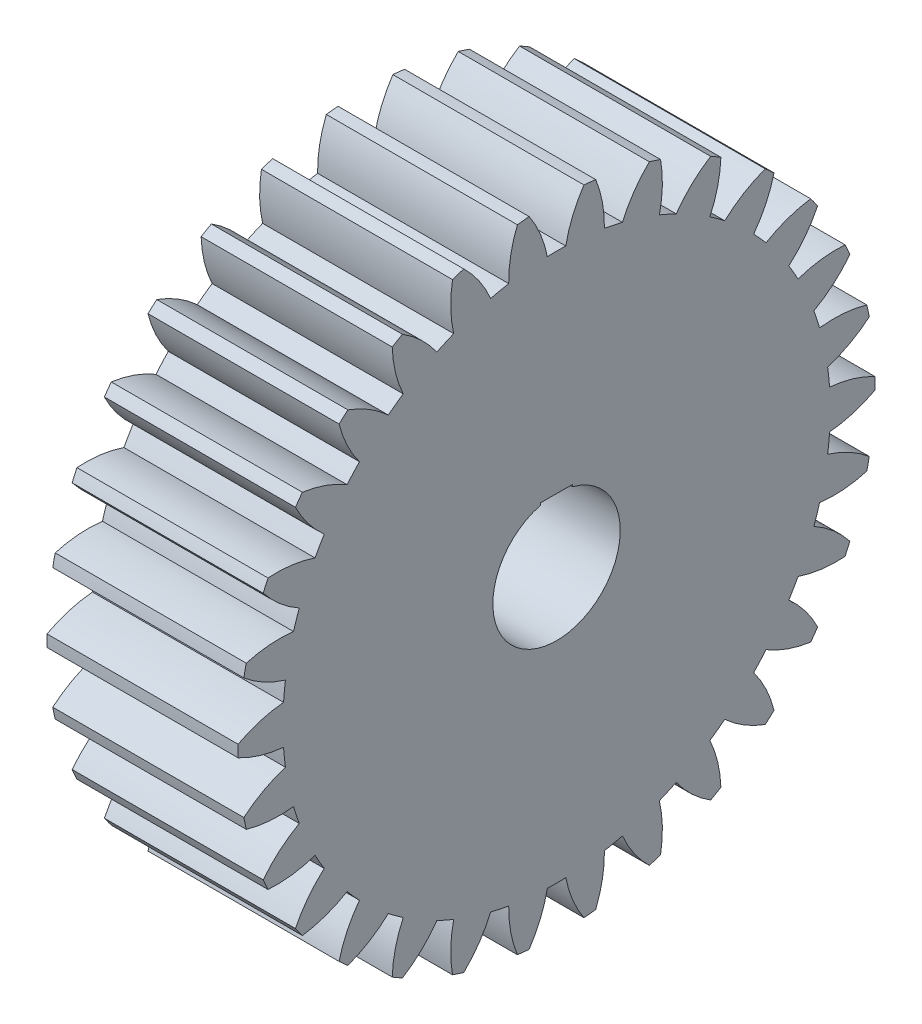
SolidWorks part; units mm, degrees
ref_plane "Plane1" through (0, 0, 0) normal (0, 0, 1) x (1, 0, 0)
ref_plane "Plane2" through (0, 0, 0) normal (0, 1, 0) x (1, 0, 0)
ref_plane "Plane3" through (0, 0, 0) normal (1, 0, 0) x (0, 0, -1)
other "Configuration Table"
sketch "HoldingSke" plane through (0, 0, 0) normal (0, 1, 0) x (1, 0, 0)
  line L0 (0, 0) -> (0.6928, -0.4)
  line L1 (-15, 0) -> (100, 0) construction
  line L2 (0, 0) -> (-2.1039, 2.3779)
  line L3 (0, 0) -> (-11.863, 4.5341)
  line L4 (0, 0) -> (7.479, 4.318)
  line L5 (0, 0) -> (-7.4956, -2.7956)
  line L6 (0, 0) -> (-9.9476, -6.7116)
  line L7 (-2.1039, 2.3779) -> (0.4791, 14.0966)
  line L8 (-76.2, 54.61) -> (-75.2, 54.61)
  line L9 (-71.009, 38.7566) -> (-53.1078, 45.2721)
  line L10 (-76.2, 71.12) -> (104.1128, 71.12)
  line L11 (0, 0) -> (-12, 0)
  line L12 (-76.2, 101.6) -> (-76.155, 101.6)
  line L13 (24.9733, 27.94) -> (52.9518, 28.4284)
  line L14 (24.9733, 27.94) -> (24.9743, 27.94)
  line L15 (24.9733, 27.94) -> (100.4006, 29.5858)
  line L16 (-63.627, -1.25) -> (-12.827, -1.25)
  circle A0 centre (0, 0) radius 3
  circle A1 centre (0, 0) radius 5
  circle A2 centre (0, 0) radius 5
  circle A3 centre (0, 0) radius 3
  dimension "MHD" = 10
  dimension "Hub_dia" = 10
  dimension "Bore" = 6
  dimension "MBD" = 6
  dimension "Num_teeth" = 30
  dimension "Pitch" = 0.8
  dimension "Overall_len" = 8
  dimension "Show_teeth" = 30
  dimension "Thickness" = 12
  dimension "OAL" = 12.0001
  dimension "T_dim" = 1
  dimension "Ap" = 20
  dimension "H" = 19.05
  dimension "Pitch_radius" = 180.3128
  dimension "Width" = 12
  dimension "Backlash" = 0.045
  dimension "Addendum_fac" = 1
  dimension "Dedendum_fac" = 1.25
  dimension "Clearance_fac" = 0.25
  dimension "Dedendum_add" = 0.001
  dimension "Module" = 1.25
sketch "BasProSke" plane through (0, 0, 0) normal (0, 1, 0) x (1, 0, 0)
  line L0 (-10, 0) -> (60, 0) construction
  line L1 (0, 0) -> (0, 20)
  line L2 (0, 0) -> (12, 0)
  line L3 (12, 0) -> (12, 20)
  line L4 (12, 20) -> (0, 20)
  dimension "Thickness" = 12
  dimension "Diameter" = 40
revolve "Base-Revolve" add sketch "BasProSke" angle 360 about L0
sketch "TooCutSke" plane through (0, 0, 0) normal (1, 0, 0) x (0, 0, -1)
  line L1 (0, 0) -> (0, 107) construction
  line L2 (0, 0) -> (-1.06, 18.72) construction
  line L3 (0, 0) -> (-3.9153, 37.2513) construction
  line L4 (-1.06, 18.72) -> (-1.9576, 18.6257) construction
  arc A0 (0.579, 17.1767) -> (-0.579, 17.1767) centre (0, 0) ccw
  arc A1 (1.7381, 19.9498) -> (-1.7381, 19.9498) centre (0, 0) ccw
  circle A2 centre (0, 0) radius 18.75 construction
  circle A3 centre (0, 0) radius 17.6192 construction
  arc A4 (-0.579, 17.1767) -> (-1.7381, 19.9498) centre (-7.9381, 15.7297) ccw
  arc A5 (1.7381, 19.9498) -> (0.579, 17.1767) centre (7.9381, 15.7297) ccw
  dimension "Root_dia" = 34.373
  dimension "Overcut_dia" = 40.0508
  dimension "Pitch_dia" = 37.5
  dimension "Base_dia" = 35.2385
  dimension "Flank_rad" = 7.5
  dimension "Half_ang" = 6
  dimension "Half_CT" = 0.9025
extrude "ToothCut" cut sketch "TooCutSke" along normal through all
fillet "Breaks" [suppressed] radius 0.025
fillet "RootFillets" [suppressed] radius 0.3135
pattern_circular "TeethCuts" count 30 every 12 about axis through (-10, 0, 0) along (1, 0, 0) of "ToothCut", "RootFillets", "Breaks"
sketch "HubNeaOneSke" plane through (0, 0, 0) normal (-1, 0, 0) x (0, 0, 1)
  circle A0 centre (0, 0) radius 5
  dimension "Diameter" = 10
extrude "HubNearOne" add sketch "HubNeaOneSke" along normal blind 5.0001
sketch "HubNeaBotSke" plane through (0, 0, 0) normal (-1, 0, 0) x (0, 0, 1)
  circle A0 centre (0, 0) radius 5
  dimension "Diameter" = 10
extrude "HubNearBoth" [suppressed] add sketch "HubNeaBotSke" along normal blind 2.5
ref_plane "FarPln" through (12, 0, 0) normal (1, 0, 0) x (0, 0, -1)
sketch "HubFarSke" plane through (12, 0, 0) normal (1, 0, 0) x (0, 0, -1)
  circle A0 centre (0, 0) radius 5
  dimension "Diameter" = 10
extrude "HubFar" [suppressed] add sketch "HubFarSke" along normal blind 2.5
sketch "BorSke" plane through (0, 0, 0) normal (1, 0, 0) x (0, 0, -1)
  circle A0 centre (0, 0) radius 3
  dimension "Diameter" = 6
extrude "Bore" cut sketch "BorSke" along normal mid plane 24.0001
sketch "KeySke" plane through (0, 0, 0) normal (1, 0, 0) x (0, 0, -1)
  line L0 (-1, 0) -> (-1, 4)
  line L1 (-1, 4) -> (1, 4)
  line L2 (1, 4) -> (1, 0)
  line L3 (0, 0) -> (0, 34) construction
  line L4 (-1, 0) -> (1, 0)
  dimension "Offset" = 4
  dimension "Width" = 2
extrude "Keyway" cut sketch "KeySke" along normal mid plane 24.0001
pattern_circular "Keyway2" [suppressed] count 2 every 90 about axis through (-10, 0, 0) along (1, 0, 0)
sketch "Sketch1" plane through (0, 4, 0) normal (0, -1, 0) x (1, 0, 0)
  line L0 (-5.0001, 0) -> (0, 0) construction
  line L1 (-5.0001, 5) -> (-5.0001, -5) construction
  line L2 (0, 0.579) -> (0, -0.579) construction
  circle A0 centre (-2.5, 0) radius 1.45
  dimension "D1" = 2.9
extrude "Cut-Extrude1" cut sketch "Sketch1" against normal blind 10
sketch "Sketch2" plane through (-5.0001, 0, 0) normal (-1, 0, 0) x (0, 0, 1)
  circle A0 centre (0, 0) radius 4
  dimension "D1" = 8
extrude "Cut-Extrude2" cut sketch "Sketch2" against normal blind 20
sketch "Sketch3" plane through (0, 0, 0) normal (-1, 0, 0) x (0, 0, 1)
  circle A0 centre (0, 0) radius 7
  arc A1 (-1, 3.873) -> (1, 3.873) centre (0, 0) ccw construction
  circle A2 centre (0, 0) radius 5
  dimension "D1" = 3
extrude "Boss-Extrude1" add sketch "Sketch3" along normal blind 5
sketch "Sketch4" plane through (0, 0, 0) normal (0, 1, 0) x (1, 0, 0)
  line L0 (-2.5, 0) -> (0, 0) construction
  line L1 (0, 0.579) -> (0, -0.579) construction
  circle A0 centre (-2.5, 0) radius 1.4
  dimension "D1" = 2.8
  dimension "D2" = 2.5
extrude "Cut-Extrude3" cut sketch "Sketch4" along normal blind 15
equation "' \"Module@HoldingSke\" = 6.35"
equation "' \"Num_teeth@HoldingSke\" = 12"
equation "' \"Ap@HoldingSke\" =  20"
equation "' \"Ap@HoldingSke\" = 20"
equation "' \"Width@HoldingSke\" = 0.5 * 25.4"
equation "' \"Hub_dia@HoldingSke\"= 1 * 25.4"
equation "' \"Hub_dia@HoldingSke\" = 1 * 25.4"
equation "' \"Overall_len@HoldingSke\" = 1.0 * 25.4"
equation "' \"Bore@HoldingSke\" = 0.75 * 25.4"
equation "' \"T_dim@HoldingSke\" = 0.1 * 25.4"
equation "' \"Width@KeySke\" = 0.25 * 25.4"
equation "' \"Show_teeth@HoldingSke\" = 13"
equation "' \"Backlash@HoldingSke\" = 0.009 * 25.4"
equation "' \"Addendum_fac@HoldingSke\" = 1.0"
equation "' \"Dedendum_fac@HoldingSke\" = 1.25"
equation "' \"Dedendum_add@HoldingSke\" = 0.00005 * 25.4"
equation "' \"Clearance_fac@HoldingSke\" = 0.25"
equation "\"Pitch@HoldingSke\" = 1 / \"Module@HoldingSke\""
equation "\"Overcut_dia@TooCutSke\" = (\"Num_teeth@HoldingSke\" + 2 * \"Addendum_fac@HoldingSke\") / \"Pitch@HoldingSke\" + 0.002 * 25.4"
equation "\"Pitch_dia@TooCutSke\" = \"Num_teeth@HoldingSke\" / \"Pitch@HoldingSke\""
equation "\"Base_dia@TooCutSke\" = \"Num_teeth@HoldingSke\" / \"Pitch@HoldingSke\" * cos((\"Ap@HoldingSke\"  * 3.14159265 / 180))"
equation "\"Root_dia@TooCutSke\" = (\"Num_teeth@HoldingSke\" + 2) / \"Pitch@HoldingSke\" - 2 * (\"Addendum_fac@HoldingSke\" + \"Dedendum_fac@HoldingSke\") / \"Pitch@HoldingSke\" - \"Dedendum_add@HoldingSke\" * 2"
equation "\"Half_ang@TooCutSke\" = 180 / \"Num_teeth@HoldingSke\""
equation "\"Half_CT@TooCutSke\" = \"Num_teeth@HoldingSke\" / \"Pitch@HoldingSke\" * sin((3.14159265 / 2 / \"Num_teeth@HoldingSke\")) / 2 - 7 * \"Backlash@HoldingSke\" / 4"
equation "\"Flank_rad@TooCutSke\" = \"Num_teeth@HoldingSke\" / \"Pitch@HoldingSke\" / 5"
equation "\"Radius@RootFillets\" = \"Clearance_fac@HoldingSke\" / \"Pitch@HoldingSke\" + \"Dedendum_add@HoldingSke\""
equation "\"Break_rad@Breaks\" = 0.02 / \"Pitch@HoldingSke\""
equation "\"Thickness@HoldingSke\" = \"Width@HoldingSke\""
equation "\"OAL@HoldingSke\" = \"Thickness@HoldingSke\""
equation "\"MHD@HoldingSke\" = (\"Num_teeth@HoldingSke\" + 2) / \"Pitch@HoldingSke\" - 2 * (\"Addendum_fac@HoldingSke\" + \"Dedendum_fac@HoldingSke\")  / \"Pitch@HoldingSke\" - \"Dedendum_add@HoldingSke\" * 2"
equation "\"MBD@HoldingSke\" = (\"Num_teeth@HoldingSke\" + 2) / \"Pitch@HoldingSke\" - 2 * (\"Addendum_fac@HoldingSke\" + \"Dedendum_fac@HoldingSke\")  / \"Pitch@HoldingSke\" - \"Dedendum_add@HoldingSke\" * 2 - 0.002 * 25.4"
equation "\"MHD@HoldingSke\" = ((sgn( \"MHD@HoldingSke\" - \"Hub_dia@HoldingSke\" )-1)*( \"MHD@HoldingSke\" - \"Hub_dia@HoldingSke\" ))/-2+ \"Hub_dia@HoldingSke\""
equation "\"MBD@HoldingSke\" = ((sgn( \"MBD@HoldingSke\" - \"Bore@HoldingSke\" )-1)*( \"MBD@HoldingSke\" - \"Bore@HoldingSke\" ))/-2+ \"Bore@HoldingSke\""
equation "\"OAL@HoldingSke\" = ((sgn( \"OAL@HoldingSke\" - \"Overall_len@HoldingSke\" )+1)*( \"OAL@HoldingSke\" - \"Overall_len@HoldingSke\" ))/2 + \"Overall_len@HoldingSke\" + 0.000002 * 25.4"
equation "\"Num_teeth@TeethCuts\" = int( \"Show_teeth@HoldingSke\" ) + 1"
equation "\"Num_teeth@TeethCuts\" = ((sgn( \"Num_teeth@TeethCuts\" - \"Num_teeth@HoldingSke\" )-1)*( \"Num_teeth@TeethCuts\" - \"Num_teeth@HoldingSke\" ))/-2+ \"Num_teeth@HoldingSke\""
equation "\"Num_teeth@TeethCuts\" = ((sgn( \"Num_teeth@TeethCuts\" - 2.0)+1)*( \"Num_teeth@TeethCuts\" - 2.0))/2 +2.0"
equation "\"Angle@TeethCuts\" = 360.0 / \"Num_teeth@HoldingSke\""
equation "\"Diameter@BasProSke\" = (\"Num_teeth@HoldingSke\" + 2 * \"Addendum_fac@HoldingSke\") / \"Pitch@HoldingSke\""
equation "\"Thickness@BasProSke\"  = \"Thickness@HoldingSke\""
equation "' \"Fillet_rad@BasProSke\" =  \"Thickness@HoldingSke\" * 0.05"
equation "' \"Fillet_rad@BasProSke\" = \"Thickness@HoldingSke\" * 0.05"
equation "\"MHD@HoldingSke\" = ((sgn( \"MHD@HoldingSke\" - \"Root_dia@TooCutSke\" )-1)*( \"MHD@HoldingSke\" - \"Root_dia@TooCutSke\" ))/-2+ \"Root_dia@TooCutSke\""
equation "\"Diameter@HubNeaOneSke\" = \"MHD@HoldingSke\""
equation "\"Length@HubNearOne\" = \"OAL@HoldingSke\" - \"Thickness@BasProSke\""
equation "\"Diameter@HubNeaBotSke\" = \"MHD@HoldingSke\""
equation "\"Length@HubNearBoth\" = ( \"OAL@HoldingSke\" - \"Thickness@BasProSke\" ) / 2.0"
equation "\"Thickness@FarPln\" = \"Thickness@BasProSke\""
equation "\"Diameter@HubFarSke\" = \"MHD@HoldingSke\""
equation "\"Length@HubFar\" = ( \"OAL@HoldingSke\" - \"Thickness@BasProSke\" ) / 2.0"
equation "\"Diameter@BorSke\" = \"MBD@HoldingSke\""
equation "\"D1@Bore\" = \"OAL@HoldingSke\" * 2.0"
equation "\"D1@Keyway\" = \"OAL@HoldingSke\" * 2.0"
equation "\"Offset@KeySke\" = \"T_dim@HoldingSke\" + \"MBD@HoldingSke\" / 2.0"
